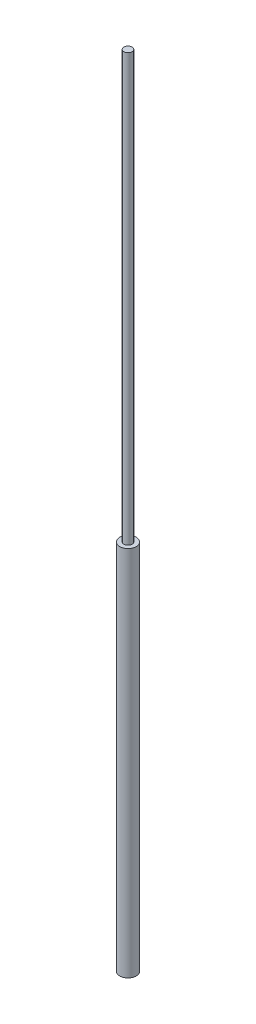
SolidWorks part; units mm, degrees
ref_plane "Front Plane" through (0, 0, 0) normal (0, 0, 1) x (1, 0, 0)
ref_plane "Top Plane" through (0, 0, 0) normal (0, 1, 0) x (1, 0, 0)
ref_plane "Right Plane" through (0, 0, 0) normal (1, 0, 0) x (0, 0, -1)
sketch "Sketch1" plane through (0, 0, 0) normal (0, 1, 0) x (1, 0, 0)
  circle A0 centre (0, 0) radius 0.75
  dimension "D1" = 1.5
extrude "Boss-Extrude1" add sketch "Sketch1" along normal blind 34
sketch "Sketch2" plane through (0, 34, 0) normal (0, 1, 0) x (1, 0, 0)
  circle A0 centre (0, 0) radius 0.375
  dimension "D1" = 0.75
extrude "Boss-Extrude2" add sketch "Sketch2" along normal blind 39
